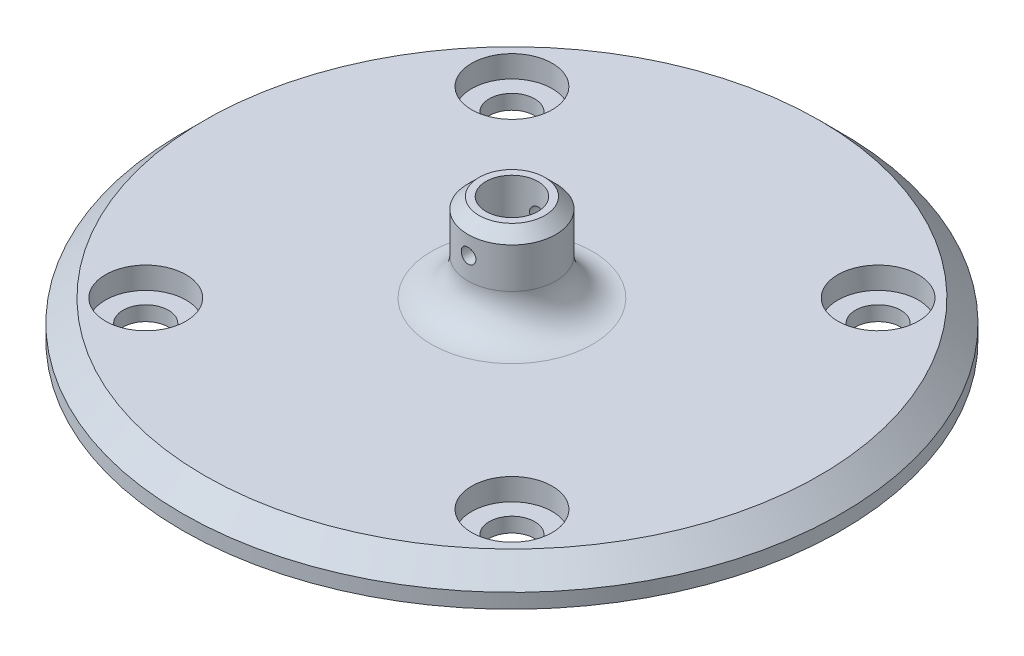
SolidWorks part; units mm, degrees
ref_plane "Front Plane" through (0, 0, 0) normal (0, 0, 1) x (1, 0, 0)
ref_plane "Top Plane" through (0, 0, 0) normal (0, 1, 0) x (1, 0, 0)
ref_plane "Right Plane" through (0, 0, 0) normal (1, 0, 0) x (0, 0, -1)
sketch "Sketch1" plane through (0, 0, 0) normal (0, 1, 0) x (1, 0, 0)
  line L1 (-31, 6) -> (31, 6) construction
  line L2 (-31, 6) -> (-31, -6) construction
  line L3 (-31, -6) -> (31, -6) construction
  line L4 (31, 6) -> (31, -6) construction
  line L5 (-31, 6) -> (31, -6) construction
  line L6 (-31, -6) -> (31, 6) construction
  circle A0 centre (-25, 0) radius 3.1 construction
  circle A1 centre (25, 0) radius 3.1 construction
  circle A2 centre (0, 0) radius 45
  circle A3 centre (-25, 25) radius 3.1 construction
  point P0 (0, 0)
  dimension "D2" = 6.2
  dimension "D7" = 90
  dimension "D1" = 12
  dimension "D3" = 6
  dimension "D4" = 25
  dimension "D5" = 25
  dimension "D6" = 25
extrude "Boss-Extrude1" add sketch "Sketch1" along normal blind 5
sketch "Sketch2" plane through (0, 5, 0) normal (0, 1, 0) x (1, 0, 0)
  circle A0 centre (25, 0) radius 3.1 construction
  circle A1 centre (-25, 0) radius 3.1 construction
  circle A2 centre (25, 0) radius 3.1 construction
  circle A3 centre (-25, 0) radius 3.1 construction
  circle A4 centre (-25, 25) radius 3.1 construction
  circle A5 centre (-25, 25) radius 3.1
extrude "Cut-Extrude1" cut sketch "Sketch2" against normal through all
sketch "Sketch8" plane through (0, 5, 0) normal (0, 1, 0) x (1, 0, 0)
  circle A0 centre (-25, 25) radius 5.5
  dimension "D1" = 11
extrude "Cut-Extrude6" cut sketch "Sketch8" against normal offset from surface (3 mm away) 2 up to face at (-25, 0, -21.9)
pattern_circular "CirPattern1" count 4 over 360 about axis through (0, 0, 0) along (0, 1, 0) of "Cut-Extrude1", "Cut-Extrude6"
sketch "Sketch3" plane through (0, 5, 0) normal (0, 1, 0) x (1, 0, 0)
  line L1 (-6, 6) -> (6, 6) construction
  line L2 (-6, 6) -> (-6, -6) construction
  line L3 (-6, -6) -> (6, -6) construction
  line L4 (6, 6) -> (6, -6) construction
  line L5 (-6, 6) -> (6, -6) construction
  line L6 (-6, -6) -> (6, 6) construction
  line L7 (-31, 6) -> (31, -6) construction
  circle A0 centre (0, 0) radius 6
  point P0 (0, 0)
  dimension "D1" = 12
extrude "Boss-Extrude2" add sketch "Sketch3" along normal blind 12
sketch "Sketch4" plane through (0, 17, 0) normal (0, 1, 0) x (1, 0, 0)
  circle A0 centre (0, 0) radius 3.55
  dimension "D1" = 7.1
extrude "Cut-Extrude2" cut sketch "Sketch4" against normal offset from surface (14 mm away) 3 up to face at (21.9, 0, -25)
sketch "Sketch5" plane through (0, 3, 0) normal (0, 1, 0) x (1, 0, 0)
  circle A0 centre (0, 0) radius 3.05
  circle A1 centre (0, 0) radius 3.55 construction
  dimension "D1" = 0.5
extrude "Cut-Extrude3" cut sketch "Sketch5" against normal through all
fillet "Fillet1" radius 5 1 edges at (0, 5, 6)
sketch "Sketch7" plane through (0, 0, 0) normal (0, 0, -1) x (-1, 0, 0)
  line L1 (6, 17) -> (-6, 17) construction
  circle A0 centre (0, 13) radius 1
  dimension "D1" = 2
  dimension "D2" = 4
extrude "Cut-Extrude5" cut sketch "Sketch7" against normal through all both and the other way through all
chamfer "Chamfer1" distance 3 angle 45 1 edges at (0, 5, 45)
chamfer "Chamfer2" distance 1.5 angle 45 1 edges at (0, 17, 6)
equation "\"D5@Sketch1\"=\"D4@Sketch1\""
